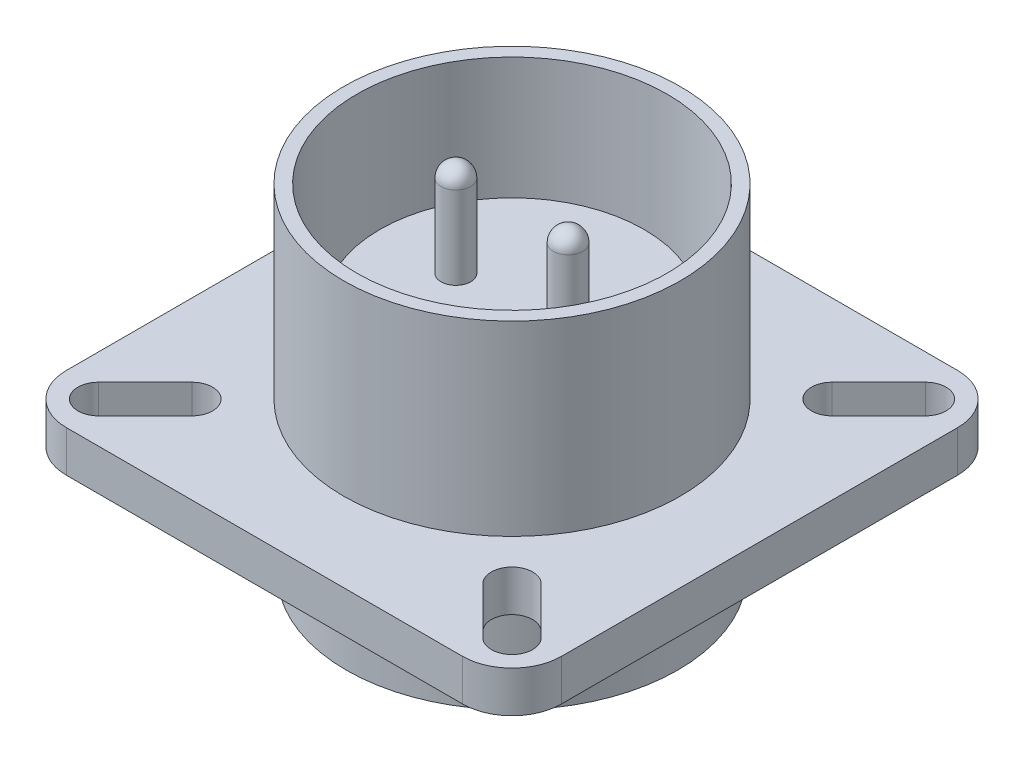
SolidWorks part; units mm, degrees
ref_plane "Front Plane" through (0, 0, 0) normal (0, 0, 1) x (1, 0, 0)
ref_plane "Top Plane" through (0, 0, 0) normal (0, 1, 0) x (1, 0, 0)
ref_plane "Right Plane" through (0, 0, 0) normal (1, 0, 0) x (0, 0, -1)
sketch "Sketch1" plane through (0, 0, 0) normal (0, 1, 0) x (1, 0, 0)
  line L0 (15, 0) -> (0, 0) construction
  line L1 (15, -15) -> (-15, -15)
  line L2 (15, -15) -> (15, 15)
  line L3 (15, 15) -> (-15, 15)
  line L4 (-15, -15) -> (-15, 15)
  line L5 (0, 0) -> (0, 15) construction
  line L6 (15, 15) -> (0, 0) construction
  line L7 (13.409, 11.6412) -> (10.5806, 8.8128)
  line L8 (11.6412, 13.409) -> (8.8128, 10.5806)
  line L9 (10.227, 11.9948) -> (11.1109, 11.1109) construction
  line L10 (-13.409, 11.6412) -> (-10.5806, 8.8128)
  line L11 (-11.6412, 13.409) -> (-8.8128, 10.5806)
  line L12 (-11.6412, -13.409) -> (-8.8128, -10.5806)
  line L13 (-13.409, -11.6412) -> (-10.5806, -8.8128)
  line L14 (11.6412, -13.409) -> (8.8128, -10.5806)
  line L15 (13.409, -11.6412) -> (10.5806, -8.8128)
  arc A0 (8.8128, 10.5806) -> (10.5806, 8.8128) centre (9.6967, 9.6967) ccw
  arc A1 (11.6412, 13.409) -> (13.409, 11.6412) centre (12.5251, 12.5251) cw
  arc A2 (-11.6412, 13.409) -> (-13.409, 11.6412) centre (-12.5251, 12.5251) ccw
  arc A3 (-8.8128, 10.5806) -> (-10.5806, 8.8128) centre (-9.6967, 9.6967) cw
  arc A4 (-8.8128, -10.5806) -> (-10.5806, -8.8128) centre (-9.6967, -9.6967) ccw
  arc A5 (-11.6412, -13.409) -> (-13.409, -11.6412) centre (-12.5251, -12.5251) cw
  arc A6 (11.6412, -13.409) -> (13.409, -11.6412) centre (12.5251, -12.5251) ccw
  arc A7 (8.8128, -10.5806) -> (10.5806, -8.8128) centre (9.6967, -9.6967) cw
  point P16 (11.9948, 10.227)
  point P23 (-11.9948, 10.227)
  point P36 (-11.9948, -10.227)
  point P37 (11.9948, -10.227)
  dimension "D4" = 4
  dimension "D1" = 30
  dimension "D2" = 30
  dimension "D3" = 2.5
  dimension "D5" = 3.5
extrude "Extrude1" add sketch "Sketch1" along normal blind 2.5
fillet "Fillet2" radius 3 4 edges at (15, 1.25, 15) (-15, 1.25, 15) (-15, 1.25, -15) (15, 1.25, -15)
sketch "Sketch3" plane through (0, 2.5, 0) normal (0, 1, 0) x (1, 0, 0)
  circle A0 centre (0, 0) radius 10.2
  circle A1 centre (0, 0) radius 9.4
  dimension "D1" = 18.8
  dimension "D2" = 0.8
extrude "Extrude2" add sketch "Sketch3" along normal blind 11.3
sketch "Sketch4" plane through (0, 2.5, 0) normal (0, 1, 0) x (1, 0, 0)
  circle A0 centre (0, 0) radius 8
  dimension "D1" = 16
extrude "Extrude3" add sketch "Sketch4" along normal blind 4.9 and the other way blind 6.7
sketch "Sketch5" plane through (0, 7.4, 0) normal (0, 1, 0) x (1, 0, 0)
  line L0 (0, 0) -> (0, 8) construction
  line L1 (-3.4, 0) -> (3.4, 0) construction
  circle A0 centre (0, 0) radius 8 construction
  circle A1 centre (3.4, 0) radius 0.9
  circle A2 centre (-3.4, 0) radius 0.9
  dimension "D1" = 1.8
  dimension "D2" = 6.8
extrude "Extrude4" add sketch "Sketch5" along normal blind 5.9 and the other way blind 17
fillet "Fillet3" radius 0.9 2 edges at (-3.4, 13.3, -0.9) (3.4, 13.3, 0.9)
sketch "Sketch6" plane through (0, 0, 0) normal (0, -1, 0) x (1, 0, 0)
  circle A0 centre (0, 0) radius 10.05
  circle A1 centre (0, 0) radius 9.55
  dimension "D1" = 20.1
  dimension "D2" = 0.5
extrude "Extrude5" add sketch "Sketch6" along normal blind 6.7
sketch "Sketch7" plane through (0, -9.6, 0) normal (0, -1, 0) x (1, 0, 0)
  line L0 (3.4, 0.6) -> (3.4, 0.9)
  line L1 (3.4, -0.6) -> (3.4, -0.9)
  line L2 (3.4, 0) -> (-3.4, 0) construction
  line L3 (0, 0) -> (0, 8) construction
  line L4 (-3.4, -0.6) -> (-3.4, -0.9)
  line L5 (-3.4, 0.6) -> (-3.4, 0.9)
  circle A1 centre (3.4, 0) radius 0.9 construction
  circle A2 centre (3.4, 0) radius 0.6
  circle A3 centre (3.4, 0) radius 0.6
  circle A4 centre (0, 0) radius 8 construction
  circle A5 centre (3.4, 0) radius 0.9
  circle A6 centre (3.4, 0) radius 0.9
  circle A7 centre (-3.4, 0) radius 0.9
  circle A8 centre (-3.4, 0) radius 0.6
  circle M3 centre (3.4, 0) radius 0.9
  dimension "D1" = 0.3
  dimension "D2" = 0
extrude "Cut-Extrude1" cut sketch "Sketch7" against normal blind 5 contours A3 | A3 L1 L0 M3 | A8 | L5 A8 L4 A7
sketch "Sketch8" plane through (0, 0, 0) normal (0, -1, 0) x (1, 0, 0)
  circle A1 centre (0, 0) radius 9.55
  circle A2 centre (0, 0) radius 9.55
  circle A3 centre (0, 0) radius 9.55 construction
  circle A4 centre (0, 0) radius 9.55
  circle A5 centre (0, 0) radius 8
  circle M2 centre (0, 0) radius 9.55
  circle M3 centre (0, 0) radius 8
  dimension "D2" = 16
  dimension "D1" = 0
extrude "Extrude7" add sketch "Sketch8" along normal blind 5.5 contours M2 M3
sketch "Sketch9" plane through (0, -5.5, 0) normal (0, -1, 0) x (1, 0, 0)
  line L0 (-5.4558, -7.8382) -> (5.4558, 7.8382) construction
  line L1 (0, 0) -> (-7.8382, 5.4558) construction
  line L2 (-4.635, -8.4095) -> (6.2765, 7.2669)
  line L3 (6.2765, 7.2669) -> (4.635, 8.4095)
  line L4 (-6.2765, -7.2669) -> (4.635, 8.4095)
  line L5 (-4.635, -8.4095) -> (-6.2765, -7.2669)
  circle A0 centre (0, 0) radius 9.55 construction
  circle A1 centre (0, 0) radius 9.55 construction
  point P14 (-0.8208, 0.5713)
  point P15 (0.8208, -0.5713)
  dimension "D1" = 1
extrude "Cut-Extrude2" cut sketch "Sketch9" against normal blind 1
